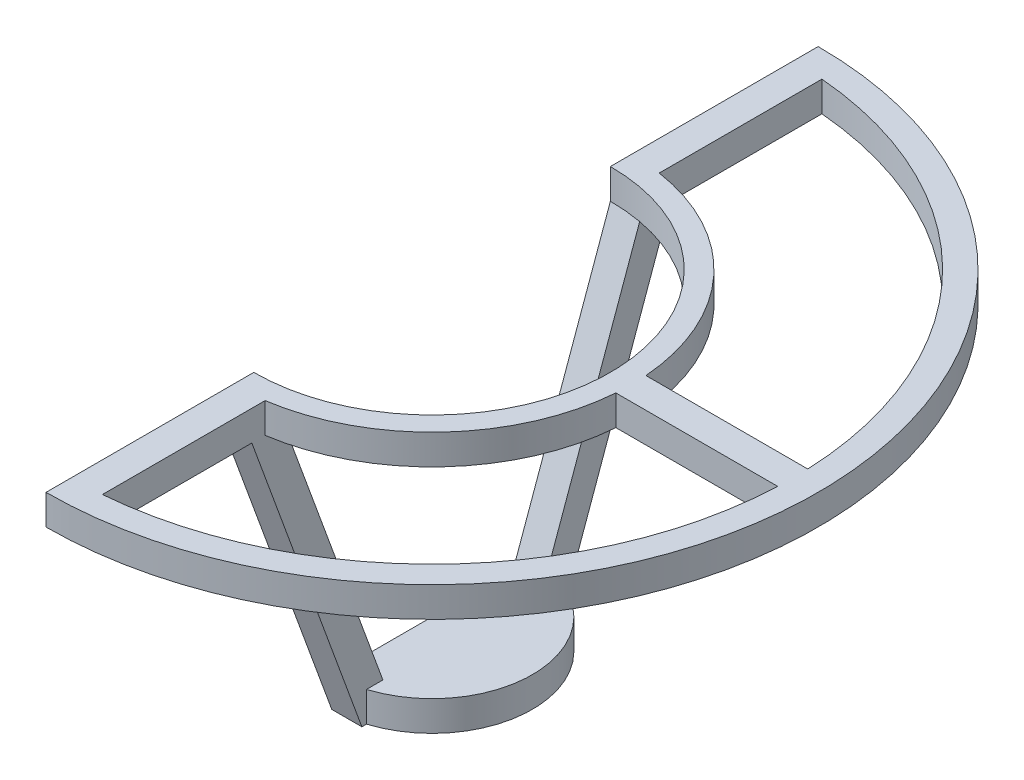
SolidWorks part; units mm, degrees
ref_plane "Front Plane" through (0, 0, 0) normal (0, 0, 1) x (1, 0, 0)
ref_plane "Top Plane" through (0, 0, 0) normal (0, 1, 0) x (1, 0, 0)
ref_plane "Right Plane" through (0, 0, 0) normal (1, 0, 0) x (0, 0, -1)
sketch "Sketch1" plane through (0, 0, 0) normal (0, 1, 0) x (1, 0, 0)
  line L1 (0, -17.78) -> (0, -38.5)
  line L2 (3, 35.8748) -> (3, 19.6523)
  line L3 (3, -19.6523) -> (3, -35.8748)
  line L4 (0, 17.78) -> (0, 38.5)
  line L5 (19.8233, 1.5) -> (35.9687, 1.5)
  line L6 (19.8233, -1.5) -> (35.9687, -1.5)
  circle A0 centre (0, 0) radius 38.5 construction
  arc A1 (0, -38.5) -> (0, 38.5) centre (0, 0) ccw
  arc A2 (0, -17.78) -> (0, 17.78) centre (0, 0) ccw
  arc A3 (3, 35.8748) -> (35.9687, 1.5) centre (0, 0) cw
  arc A4 (3, 19.6523) -> (19.8233, 1.5) centre (0, 0) cw
  arc A5 (19.8233, -1.5) -> (3, -19.6523) centre (0, 0) cw
  arc A6 (35.9687, -1.5) -> (3, -35.8748) centre (0, 0) cw
  point P8 (17.78, 0)
  dimension "D1" = 77
  dimension "D2" = 17.78
  dimension "D3" = 3
  dimension "D4" = 19.88
  dimension "D5" = 36
  dimension "D7" = 3
  dimension "D8" = 3
extrude "Boss-Extrude2" add sketch "Sketch1" along normal blind 3
ref_plane "Plane1" through (0, -30, 0) normal (0, -1, 0) x (-1, 0, 0)
sketch "Sketch4" plane through (0, -30, 0) normal (0, -1, 0) x (-1, 0, 0)
  line L0 (0, 10) -> (0, -10)
  arc A0 (0, 10) -> (0, -10) centre (0, 0) ccw
  dimension "D1" = 10
extrude "Boss-Extrude3" add sketch "Sketch4" against normal blind 3 separate body
sketch "Sketch6" plane through (0, 0, 0) normal (1, 0, 0) x (0, 0, -1)
  line L1 (-10, -27) -> (10, -27) construction
  line L3 (-21.725, -30) -> (21.725, -30) construction
  line L10 (38.5, 0) -> (17.78, 0) construction
  line L15 (20.78, 0) -> (10, -30)
  line L16 (17.78, 0) -> (8.078, -27)
  line L17 (8.078, -27) -> (8.078, -30)
  line L18 (8.078, -30) -> (10, -30)
  line L19 (20.78, 0) -> (17.78, 0)
  line L20 (-20.9744, 0) -> (-10, -30)
  line L21 (-17.78, 0) -> (-38.5, 0) construction
  line L22 (-17.78, 0) -> (-7.903, -27)
  line L23 (-17.78, 0) -> (-20.9744, 0)
  line L24 (-7.903, -27) -> (-7.903, -30)
  line L25 (-10, -30) -> (10, -30) construction
  line L26 (-7.903, -30) -> (-10, -30)
  dimension "D3" = 0
  dimension "D1" = 3
  dimension "D2" = 3
extrude "Boss-Extrude4" add sketch "Sketch6" along normal blind 3
